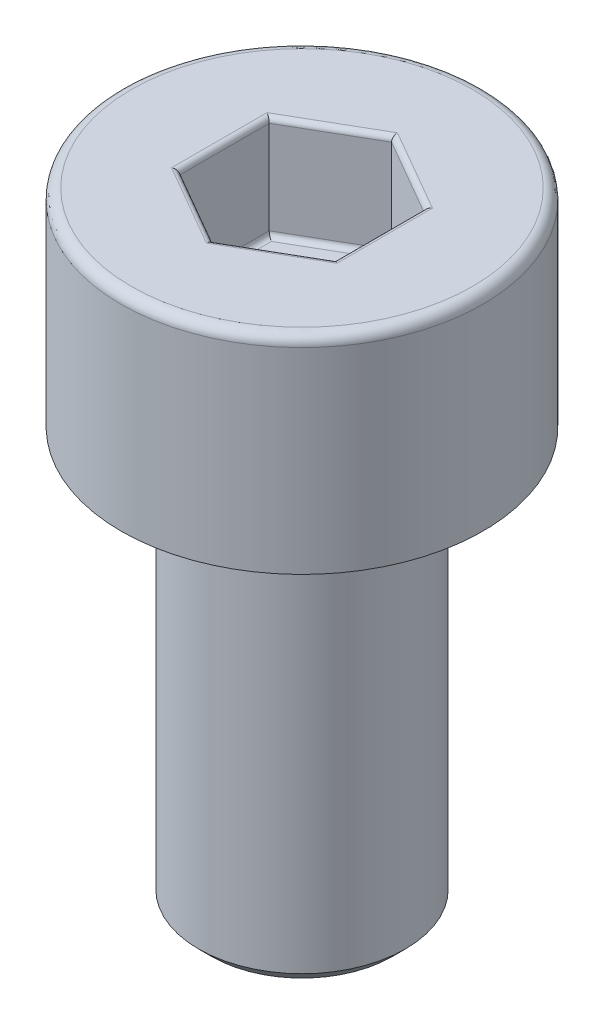
SolidWorks part; units mm, degrees
ref_plane "Front Plane" through (0, 0, 0) normal (0, 0, 1) x (1, 0, 0)
ref_plane "Top Plane" through (0, 0, 0) normal (0, 1, 0) x (1, 0, 0)
ref_plane "Right Plane" through (0, 0, 0) normal (1, 0, 0) x (0, 0, -1)
sketch "Sketch1" plane through (0, 0, 0) normal (0, 0, 1) x (1, 0, 0)
  line L0 (0, 0) -> (0, -47.0967) construction
  line L1 (0, -12) -> (-2, -12)
  line L2 (-2, -12) -> (-2, -4)
  line L3 (-2, -4) -> (-3.5, -4)
  line L4 (-3.5, -4) -> (-3.5, 0)
  line L5 (-3.5, 0) -> (0, 0)
  line L6 (0, 0) -> (0, -12)
  dimension "D1" = 8
  dimension "d" = 4
  dimension "k" = 4
  dimension "dk" = 7
revolve "Revolve1" add sketch "Sketch1" angle 360 about L0
chamfer "Chamfer1" distance 0.25 angle 45 2 edges at (0, -4, 2) (0, -12, 2)
fillet "Fillet1" radius 0.2 1 edges at (0, 0, 3.5)
sketch "Sketch2" plane through (0, 0, 0) normal (0, 1, 0) x (1, 0, 0)
  line L1 (0, 1.7321) -> (-1.5, 0.866)
  line L2 (-1.5, 0.866) -> (-1.5, -0.866)
  line L3 (-1.5, -0.866) -> (0, -1.7321)
  line L4 (0, -1.7321) -> (1.5, -0.866)
  line L5 (1.5, -0.866) -> (1.5, 0.866)
  line L6 (1.5, 0.866) -> (0, 1.7321)
  circle A0 centre (0, 0) radius 1.5 construction
  dimension "s" = 3
extrude "Cut-Extrude1" cut sketch "Sketch2" against normal blind 2
fillet "Fillet2" radius 0.1 12 edges at (-0.75, 0, -1.299) (-1.5, 0, 0) (-0.75, 0, 1.299) (0.75, 0, 1.299) (1.5, 0, 0) (0.75, 0, -1.299) (1.5, -2, 0) (0.75, -2, 1.299) (-0.75, -2, 1.299) (-1.5, -2, 0) (-0.75, -2, -1.299) (0.75, -2, -1.299)
